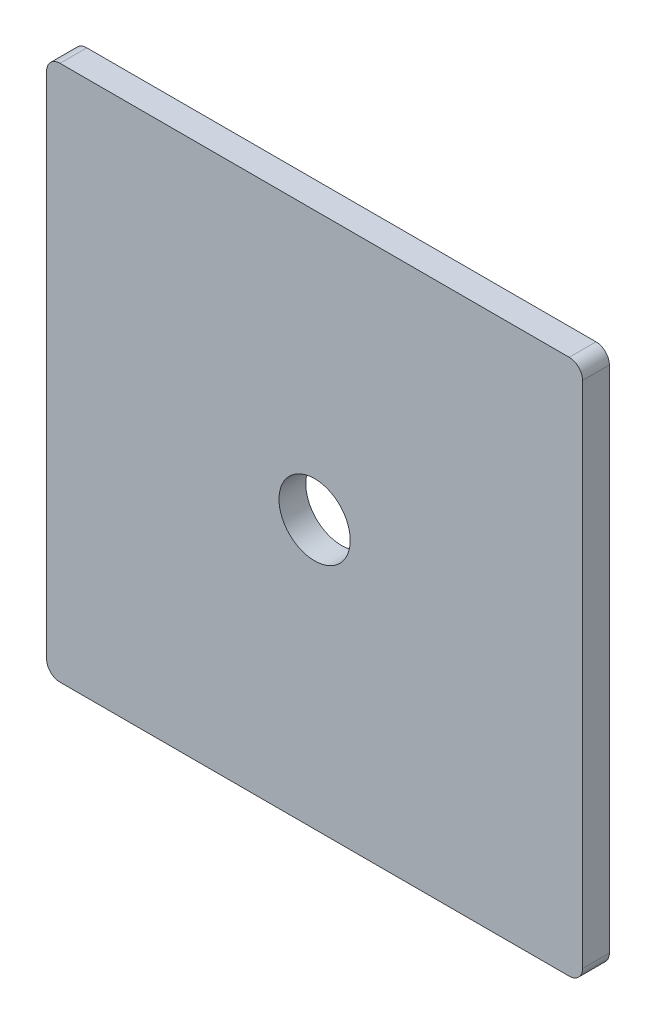
SolidWorks part; units mm, degrees
ref_plane "前视基准面" through (0, 0, 0) normal (0, 0, 1) x (1, 0, 0)
ref_plane "上视基准面" through (0, 0, 0) normal (0, 1, 0) x (1, 0, 0)
ref_plane "右视基准面" through (0, 0, 0) normal (1, 0, 0) x (0, 0, -1)
ref_plane "基准面1" through (0, 0, 3.15) normal (0, 0, -1) x (-1, 0, 0)
sketch "草图1" plane through (0, 0, 3.15) normal (0, 0, -1) x (-1, 0, 0)
  line L0 (-2.85, -3) -> (2.85, -3)
  line L1 (3, -2.85) -> (3, 2.85)
  line L2 (2.85, 3) -> (-2.85, 3)
  line L3 (-3, 2.85) -> (-3, -2.85)
  arc A0 (-3, -2.85) -> (-2.85, -3) centre (-2.85, -2.85) ccw
  arc A1 (2.85, -3) -> (3, -2.85) centre (2.85, -2.85) ccw
  arc A2 (3, 2.85) -> (2.85, 3) centre (2.85, 2.85) ccw
  arc A3 (-2.85, 3) -> (-3, 2.85) centre (-2.85, 2.85) ccw
extrude "凸台-拉伸1" add sketch "草图1" against normal blind 0.3
sketch "草图2" plane through (0, 0, 3.45) normal (0, 0, 1) x (1, 0, 0)
  circle A0 centre (0, 0) radius 0.3988
extrude "切除-拉伸1" cut sketch "草图2" against normal blind 10
